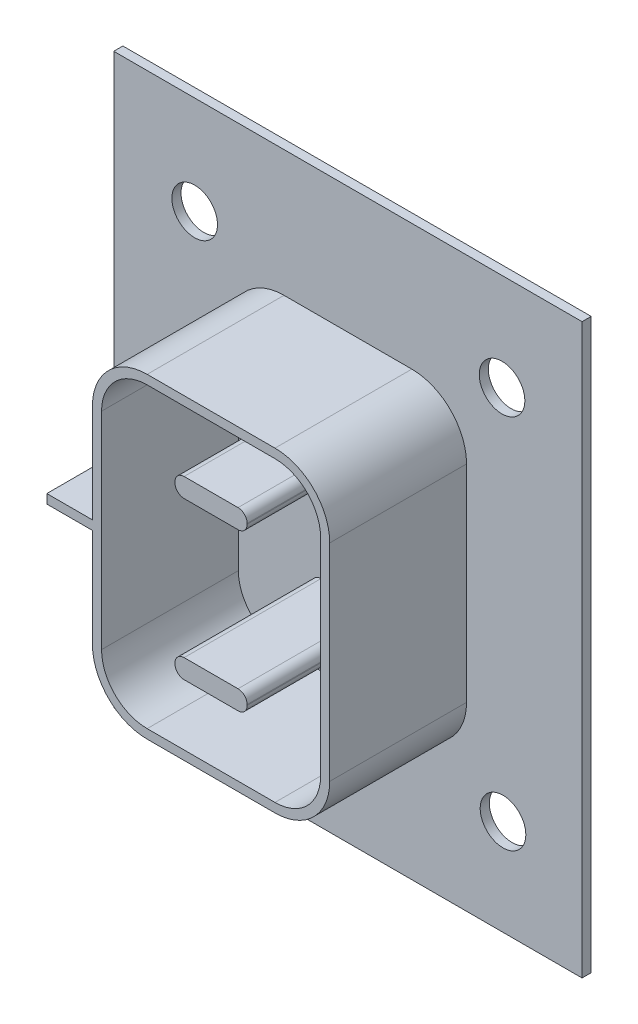
SolidWorks part; units mm, degrees
other "相机1"
ref_plane "前视基准面" through (0, 0, 0) normal (0, 0, 1) x (1, 0, 0)
ref_plane "上视基准面" through (0, 0, 0) normal (0, 1, 0) x (1, 0, 0)
ref_plane "右视基准面" through (0, 0, 0) normal (1, 0, 0) x (0, 0, -1)
sketch "草图1" plane through (0, 0, 0) normal (0, 0, 1) x (1, 0, 0)
  line L0 (-14.0112, 34.6331) -> (14.0112, 34.6331)
  line L1 (-14.0112, 32.6331) -> (14.0112, 32.6331)
  line L2 (-24.0112, 22.6331) -> (-24.0112, -22.6331)
  line L3 (-14.0112, -32.6331) -> (14.0112, -32.6331)
  line L4 (24.0112, 22.6331) -> (24.0112, -22.6331)
  line L5 (-24.0112, 32.6331) -> (24.0112, -32.6331) construction
  line L6 (-24.0112, -32.6331) -> (24.0112, 32.6331) construction
  line L7 (26.0112, 22.6331) -> (26.0112, -22.6331)
  line L8 (-14.0112, -34.6331) -> (14.0112, -34.6331)
  line L9 (-26.0112, 22.6331) -> (-26.0112, 1)
  line L10 (-26.0112, -1) -> (-26.0112, -22.6331)
  line L11 (-26.0112, 1) -> (-36.0112, 1)
  line L12 (-7.9084, 0) -> (14.0112, 0) construction
  line L13 (-26.0112, -1) -> (-36.0112, -1)
  line L14 (-36.0112, 1) -> (-36.0112, -1)
  line L15 (-26.0112, 1) -> (-36.0112, -1) construction
  line L16 (-26.0112, -1) -> (-36.0112, 1) construction
  line L17 (-5.9084, 19.2914) -> (5.9084, 19.2914)
  line L18 (-26.0112, 22.6331) -> (-26.0112, -22.6331) construction
  line L19 (-7.9084, 17.2914) -> (-7.9084, 17.0991)
  line L20 (-5.9084, 15.0991) -> (5.9084, 15.0991)
  line L21 (7.9084, 17.2914) -> (7.9084, 17.0991)
  line L22 (-7.9084, 19.2914) -> (7.9084, 15.0991) construction
  line L23 (-7.9084, 15.0991) -> (7.9084, 19.2914) construction
  line L24 (-7.9084, -15.0991) -> (7.9084, -19.2914) construction
  line L25 (-7.9084, -19.2914) -> (7.9084, -15.0991) construction
  line L26 (7.9084, -17.2914) -> (7.9084, -17.0991)
  line L27 (-5.9084, -15.0991) -> (5.9084, -15.0991)
  line L28 (-7.9084, -17.2914) -> (-7.9084, -17.0991)
  line L29 (-5.9084, -19.2914) -> (5.9084, -19.2914)
  arc A0 (-14.0112, -32.6331) -> (-24.0112, -22.6331) centre (-14.0112, -22.6331) cw
  arc A1 (14.0112, -32.6331) -> (24.0112, -22.6331) centre (14.0112, -22.6331) ccw
  arc A2 (24.0112, 22.6331) -> (14.0112, 32.6331) centre (14.0112, 22.6331) ccw
  arc A3 (-24.0112, 22.6331) -> (-14.0112, 32.6331) centre (-14.0112, 22.6331) cw
  arc A4 (26.0112, 22.6331) -> (14.0112, 34.6331) centre (14.0112, 22.6331) ccw
  arc A5 (14.0112, -34.6331) -> (26.0112, -22.6331) centre (14.0112, -22.6331) ccw
  arc A6 (-14.0112, -34.6331) -> (-26.0112, -22.6331) centre (-14.0112, -22.6331) cw
  arc A7 (-26.0112, 22.6331) -> (-14.0112, 34.6331) centre (-14.0112, 22.6331) cw
  arc A8 (-7.9084, 17.2914) -> (-5.9084, 19.2914) centre (-5.9084, 17.2914) cw
  arc A9 (-7.9084, 17.0991) -> (-5.9084, 15.0991) centre (-5.9084, 17.0991) ccw
  arc A10 (5.9084, 15.0991) -> (7.9084, 17.0991) centre (5.9084, 17.0991) ccw
  arc A11 (5.9084, 19.2914) -> (7.9084, 17.2914) centre (5.9084, 17.2914) cw
  arc A12 (5.9084, -19.2914) -> (7.9084, -17.2914) centre (5.9084, -17.2914) ccw
  arc A13 (5.9084, -15.0991) -> (7.9084, -17.0991) centre (5.9084, -17.0991) cw
  arc A14 (-7.9084, -17.0991) -> (-5.9084, -15.0991) centre (-5.9084, -17.0991) cw
  arc A15 (-7.9084, -17.2914) -> (-5.9084, -19.2914) centre (-5.9084, -17.2914) ccw
  point P0 (0, 0)
  point P34 (-31.0112, 0)
  point P35 (0, 17.1953)
  point P70 (0, -17.1953)
  dimension "D1" = 10
  dimension "D5" = 2
  dimension "D2" = 2
  dimension "D3" = 10
  dimension "D4" = 2
extrude "凸台-拉伸1" add sketch "草图1" along normal blind 30 contours A7 L9 L11 L14 L13 L10 A6 L8 A5 L7 A4 L0 L2 A3 L1 A2 L4 A1 L3 A0 | A11 L17 A8 L19 A9 L20 A10 L21 | L28 A15 L29 A12 L26 A13 L27 A14
sketch "草图2" plane through (0, 0, 0) normal (0, 0, 1) x (1, 0, 0)
  line L1 (-51.3344, 62.3066) -> (51.3344, 62.3066)
  line L2 (-51.3344, 62.3066) -> (-51.3344, -62.3066)
  line L3 (-51.3344, -62.3066) -> (51.3344, -62.3066)
  line L4 (51.3344, 62.3066) -> (51.3344, -62.3066)
  line L5 (-51.3344, 62.3066) -> (51.3344, -62.3066) construction
  line L6 (-51.3344, -62.3066) -> (51.3344, 62.3066) construction
  circle A0 centre (-33.978, -41.2405) radius 5
  circle A1 centre (34.0024, -41.2701) radius 5
  circle A2 centre (33.7886, 41.0106) radius 5
  circle A3 centre (-33.5912, 40.771) radius 5
  point P0 (0, 0)
extrude "凸台-拉伸2" add sketch "草图2" against normal blind 2
